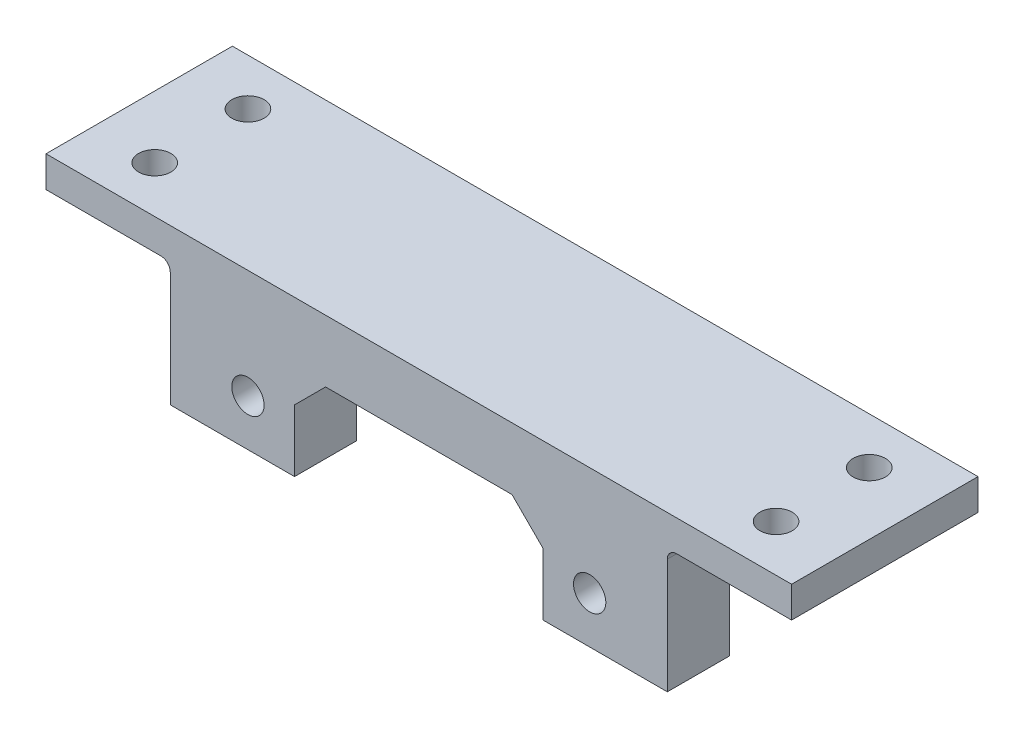
SolidWorks part; units mm, degrees
ref_plane "前视基准面" through (0, 0, 0) normal (0, 0, 1) x (1, 0, 0)
ref_plane "上视基准面" through (0, 0, 0) normal (0, 1, 0) x (1, 0, 0)
ref_plane "右视基准面" through (0, 0, 0) normal (1, 0, 0) x (0, 0, -1)
sketch "草图1" plane through (0, 0, 0) normal (0, 0, 1) x (1, 0, 0)
  line L0 (20, 0) -> (20, -20)
  line L1 (0, 0) -> (20, 0)
  line L2 (0, 0) -> (0, 5)
  line L3 (0, 5) -> (120, 5)
  line L4 (120, 0) -> (120, 5)
  line L5 (20, -20) -> (40, -20)
  line L6 (40, -20) -> (40, -5)
  line L7 (80, -5) -> (80, -20)
  line L8 (80, -20) -> (100, -20)
  line L9 (100, -20) -> (100, 0)
  line L10 (40, -5) -> (80, -5)
  line L11 (100, 0) -> (120, 0)
  dimension "D1" = 120
  dimension "D2" = 5
  dimension "D3" = 20
  dimension "D4" = 20
  dimension "D5" = 20
  dimension "D6" = 20
  dimension "D9" = 5
extrude "凸台-拉伸1" add sketch "草图1" along normal blind 30 contours L5 L6 L1 L0 | L1 L4 L3 L2 | L8 L9 L1 L7
chamfer "倒角2" distance 5 angle 45 2 edges at (80, -5, 15) (40, -5, 15)
sketch "草图2" plane through (0, 5, 0) normal (0, 1, 0) x (1, 0, 0)
  line L0 (0, -30) -> (0, 0) construction
  line L2 (0, -30) -> (120, -30) construction
  circle A0 centre (10, -7.5) radius 2.6
  circle A1 centre (10, -22.5) radius 2.6
  circle A2 centre (110, -22.5) radius 2.6
  circle A3 centre (110, -7.5) radius 2.6
  dimension "D7" = 5.2
  dimension "D8" = 5.2
  dimension "D1" = 10
  dimension "D2" = 10
  dimension "D3" = 2
  dimension "D5" = 15
  dimension "D6" = 7.5
extrude "切除-拉伸1" cut sketch "草图2" against normal through all
sketch "草图3" plane through (20, 0, 0) normal (-1, 0, 0) x (0, 0, 1)
  line L0 (10, -20) -> (10, -5)
  line L1 (30, -20) -> (0, -20) construction
  line L2 (10, -5) -> (20, -5)
  line L3 (20, -5) -> (20, -20)
  line L4 (20, -20) -> (10, -20)
  line L5 (30, 0) -> (30, -20) construction
  dimension "D1" = 10
  dimension "D2" = 15
  dimension "D3" = 10
extrude "切除-拉伸2" cut sketch "草图3" against normal through all
sketch "草图4" plane through (0, 0, 0) normal (0, 0, -1) x (-1, 0, 0)
  line L0 (-80, -10) -> (-80, -20) construction
  line L1 (-80, -20) -> (-100, -20) construction
  circle A0 centre (-87.5, -12.5) radius 2.6
  circle A1 centre (-32.5, -12.5) radius 2.6
  dimension "D1" = 5.2
  dimension "D2" = 7.5
  dimension "D3" = 7.5
  dimension "D4" = 2
extrude "切除-拉伸3" cut sketch "草图4" against normal through all
fillet "圆角1" radius 1.5 2 edges at (20, 0, 15) (100, 0, 15)
